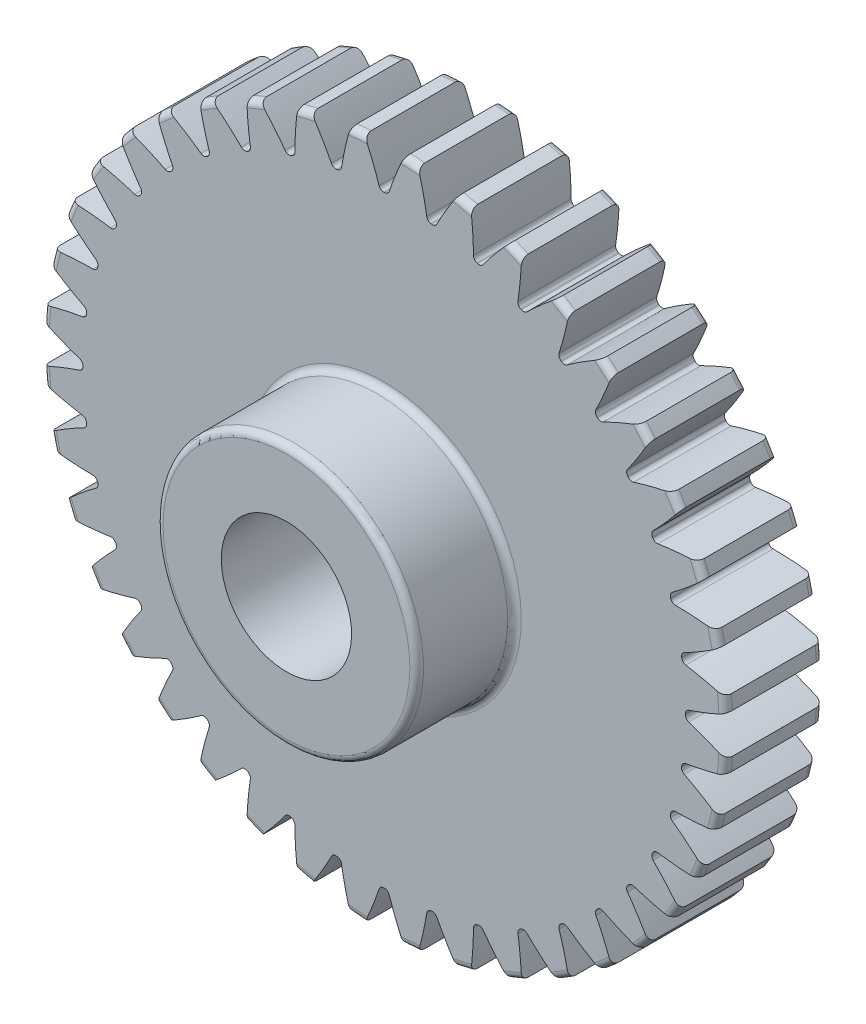
SolidWorks part; units mm, degrees
ref_plane "Front Plane" through (0, 0, 0) normal (0, 0, 1) x (1, 0, 0)
ref_plane "Top Plane" through (0, 0, 0) normal (0, 1, 0) x (1, 0, 0)
ref_plane "Right Plane" through (0, 0, 0) normal (1, 0, 0) x (0, 0, -1)
sketch "Sketch1" plane through (0, 0, 0) normal (0, 0, 1) x (1, 0, 0)
  line L0 (-508, 0) -> (508, 0) construction
  circle A0 centre (0, 0) radius 21 construction
  circle A1 centre (0, 0) radius 20 construction
  circle A2 centre (0, 0) radius 18.5 construction
  circle A3 centre (0, 0) radius 8 construction
  circle A4 centre (0, 0) radius 4 construction
  dimension "D1" = 2.5
  dimension "OD" = 42
  dimension "Pitch Dia." = 40
  dimension "D2" = 1
  dimension "D3" = 2.5
  dimension "Root Dia." = 37
  dimension "Hub Dia." = 16
  dimension "Shaft Dia." = 8
  dimension "Number of Teeth" = 1016
sketch "Sketch2" plane through (0, 0, 0) normal (1, 0, 0) x (0, 0, -1)
  line L0 (0, 0) -> (-6, 0) construction
  line L1 (-6, 0) -> (-12, 0) construction
  dimension "Overall Width" = 12
  dimension "Face Width" = 6
sketch "Sketch4" plane through (0, 0, 0) normal (1, 0, 0) x (0, 0, -1)
  line L0 (-12, 4) -> (-12, 8)
  line L1 (-12, 8) -> (-6, 8)
  line L2 (-6, 8) -> (-6, 21)
  line L3 (-6, 21) -> (0, 21)
  line L4 (0, 21) -> (0, 4)
  line L5 (-6, 8) -> (-6, 0) construction
  line L6 (0, 21) -> (0, -21) construction
  line L7 (-6, 8) -> (0, 8) construction
  line L12 (-12, 4) -> (0, 4)
revolve "Revolve1" add sketch "Sketch4" angle 360 about L1
fillet "Fillet2" radius 0.42 4 edges at (0, 8, 12) (0, 8, 6) (0, 21, 6) (0, 21, 0)
sketch "Sketch7" plane through (0, 0, 6) normal (0, 0, 1) x (1, 0, 0)
  line L0 (0, 0) -> (0, 21) construction
  line L1 (0.7852, 19.9846) -> (1.1869, 20.9664) construction
  line L3 (1.6476, 20.9353) -> (1.5692, 19.9383) construction
  line L4 (1.5692, 19.9383) -> (1.4515, 18.443) construction
  line L5 (0, 0) -> (1.4515, 18.443) construction
  line L6 (0.7852, 19.9846) -> (0, 0) construction
  line L7 (0.7852, 19.9846) -> (0.8245, 20.9838) construction
  line L8 (0.7852, 19.9846) -> (0, 0) construction
  circle A0 centre (0, 0) radius 21 construction
  arc A1 (-0.027, 18.5) -> (0.027, 18.5) centre (0, 0) cw
  circle A2 centre (0, 0) radius 18.5 construction
  arc A3 (-0.7852, 19.9846) -> (0.7852, 19.9846) centre (0, 0) cw construction
  circle A4 centre (0, 0) radius 20 construction
  arc A5 (2.0774, 20.897) -> (1.2172, 20.9647) centre (0, 0) ccw construction
  arc A6 (0.7852, 19.9846) -> (2.3507, 19.8614) centre (0, 0) cw construction
  arc A7 (-1.2172, 20.9647) -> (1.2172, 20.9647) centre (0, 0) cw
  arc A8 (0.3122, 18.7056) -> (1.2172, 20.9647) centre (19.296, 12.4116) cw
  arc A9 (-0.3122, 18.7056) -> (-1.2172, 20.9647) centre (-19.296, 12.4116) ccw
  arc A10 (-0.027, 18.5) -> (-0.3122, 18.7056) centre (-0.0274, 18.8) cw
  arc A11 (0.027, 18.5) -> (0.3122, 18.7056) centre (0.0274, 18.8) ccw
  point P26 (-0.2447, 18.4984)
  point P29 (0.2447, 18.4984)
  dimension "D4" = 0.3
  dimension "D5" = 20
  dimension "D2" = 1.5708
  dimension "D1" = 3.1416
  dimension "D3" = 20
extrude "Cut-Extrude2" cut sketch "Sketch7" against normal through all
pattern_circular "CirPattern1" count 40 over 360 about axis through (0, 0, 0) along (0, 0, 1) of "Cut-Extrude2"
equation "\"D1@Sketch1\"=2.5*(\"Pitch Dia.@Sketch1\"/\"Number of Teeth@Sketch1\")"
equation "\"D1@CirPattern1\"=\"Number of Teeth@Sketch1\""
equation "\"D1@Fillet2\"=\"OD@Sketch1\"*.01"
equation "\"D1@Sketch7\"=3.14159*(\"Pitch Dia.@Sketch1\"/\"Number of Teeth@Sketch1\")"
equation "\"D2@Sketch7\"=\"D1@Sketch7\"/2"
equation "\"D4@Sketch7\"=\"D1@Sketch7\"*.0955"
equation "\"D5@Sketch7\"=\"Pitch Dia.@Sketch1\"/2"
